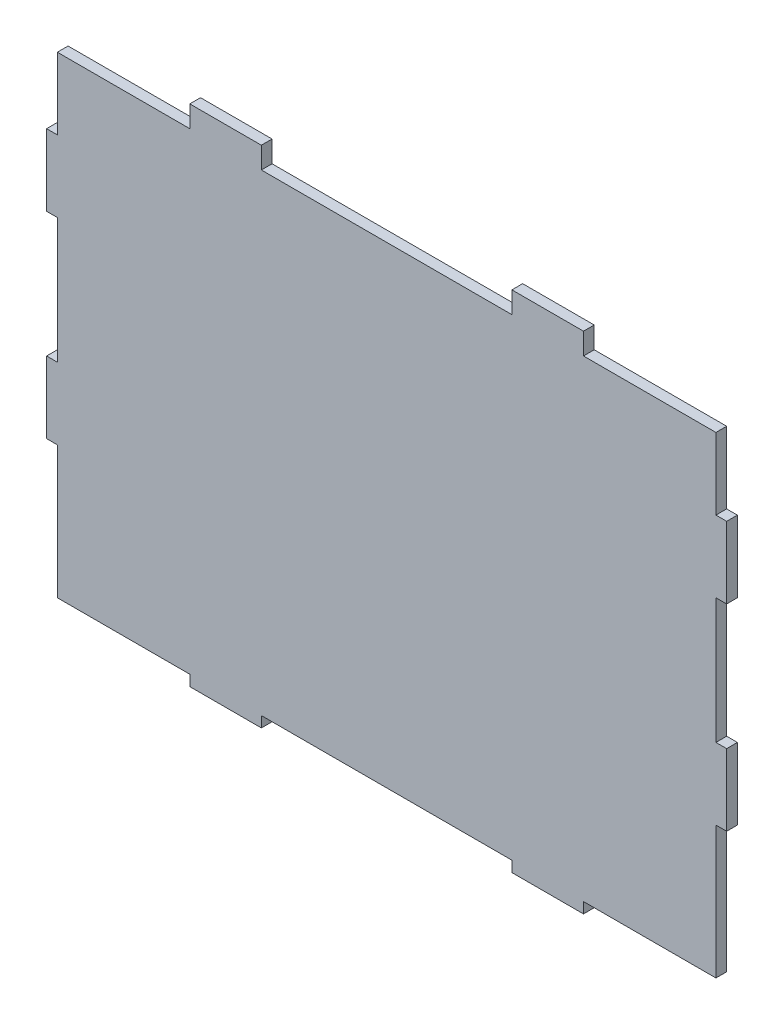
SolidWorks part; units mm, degrees
ref_plane "Спереди" through (0, 0, 0) normal (0, 0, 1) x (1, 0, 0)
ref_plane "Сверху" through (0, 0, 0) normal (0, 1, 0) x (1, 0, 0)
ref_plane "Справа" through (0, 0, 0) normal (1, 0, 0) x (0, 0, -1)
sketch "Эскиз2" plane through (0, 0, 0) normal (0, 0, 1) x (1, 0, 0)
  line L0 (0, 112) -> (0, 132)
  line L5 (0, 0) -> (37, 0)
  line L6 (0, 0) -> (0, 37)
  line L7 (0, 132) -> (37, 132)
  line L8 (184, 0) -> (184, 37)
  line L10 (37, 132) -> (37, 138)
  line L11 (37, 138) -> (57, 138)
  line L12 (57, 132) -> (57, 138)
  line L14 (127, 132) -> (127, 138)
  line L15 (127, 138) -> (147, 138)
  line L16 (147, 132) -> (147, 138)
  line L17 (184, 112) -> (187, 112)
  line L19 (184, 92) -> (187, 92)
  line L20 (187, 112) -> (187, 92)
  line L21 (184, 57) -> (187, 57)
  line L23 (184, 37) -> (187, 37)
  line L24 (187, 57) -> (187, 37)
  line L26 (147, 0) -> (147, -3)
  line L27 (147, -3) -> (127, -3)
  line L28 (127, 0) -> (127, -3)
  line L30 (57, 0) -> (57, -3)
  line L31 (57, -3) -> (37, -3)
  line L32 (37, 0) -> (37, -3)
  line L33 (0, 37) -> (-3, 37)
  line L35 (0, 57) -> (-3, 57)
  line L36 (-3, 37) -> (-3, 57)
  line L37 (0, 92) -> (-3, 92)
  line L39 (0, 112) -> (-3, 112)
  line L40 (-3, 92) -> (-3, 112)
  line L41 (57, 132) -> (127, 132)
  line L42 (147, 132) -> (184, 132)
  line L43 (184, 112) -> (184, 132)
  line L44 (184, 57) -> (184, 92)
  line L45 (147, 0) -> (184, 0)
  line L46 (57, 0) -> (127, 0)
  line L47 (0, 57) -> (0, 92)
  dimension "D1" = 184
  dimension "D2" = 132
  dimension "D3" = 20
  dimension "D4" = 20
  dimension "D5" = 20
  dimension "D6" = 20
  dimension "D7" = 20
  dimension "D8" = 35
  dimension "D9" = 6
  dimension "D10" = 3
  dimension "D11" = 3
  dimension "D12" = 3
  dimension "D13" = 37
  dimension "D14" = 70
extrude "Бобышка-Вытянуть1" add sketch "Эскиз2" along normal blind 3
